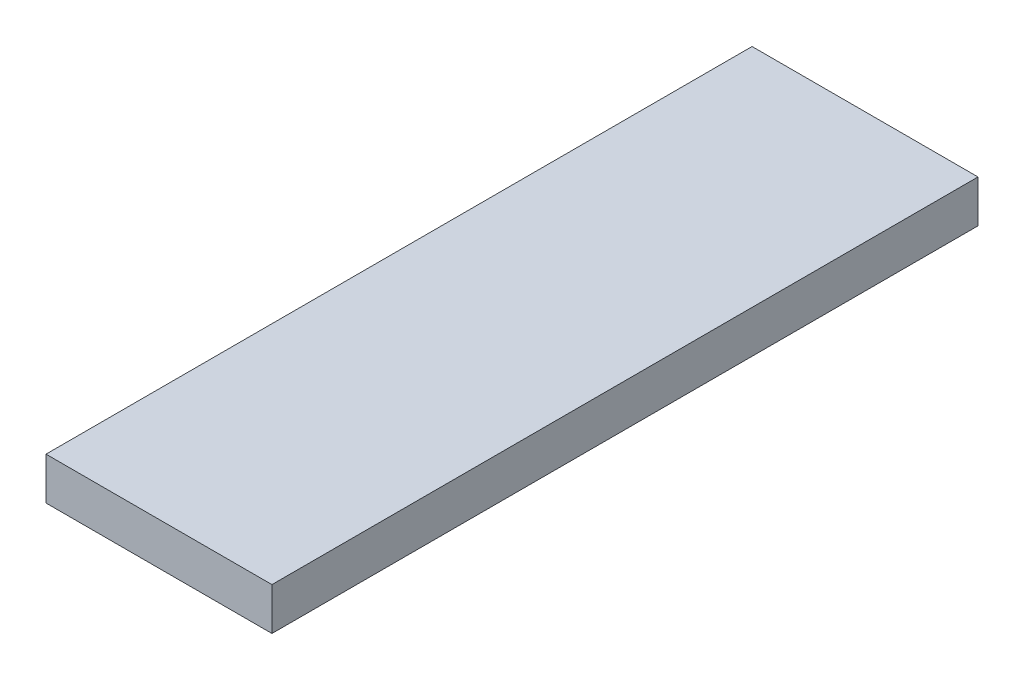
SolidWorks part; units mm, degrees
ref_plane "前视基准面" through (0, 0, 0) normal (0, 0, 1) x (1, 0, 0)
ref_plane "上视基准面" through (0, 0, 0) normal (0, 1, 0) x (1, 0, 0)
ref_plane "右视基准面" through (0, 0, 0) normal (1, 0, 0) x (0, 0, -1)
sketch "Sketch1" plane through (0, 0, 0) normal (0, 1, 0) x (1, 0, 0)
  line L1 (8, -25) -> (-8, -25)
  line L2 (8, -25) -> (8, 25)
  line L3 (8, 25) -> (-8, 25)
  line L4 (-8, -25) -> (-8, 25)
  line L5 (8, -25) -> (-8, 25) construction
  line L6 (8, 25) -> (-8, -25) construction
  point P0 (0, 0)
  dimension "D1" = 16
  dimension "D2" = 50
extrude "Boss-Extrude1" add sketch "Sketch1" along normal blind 3
